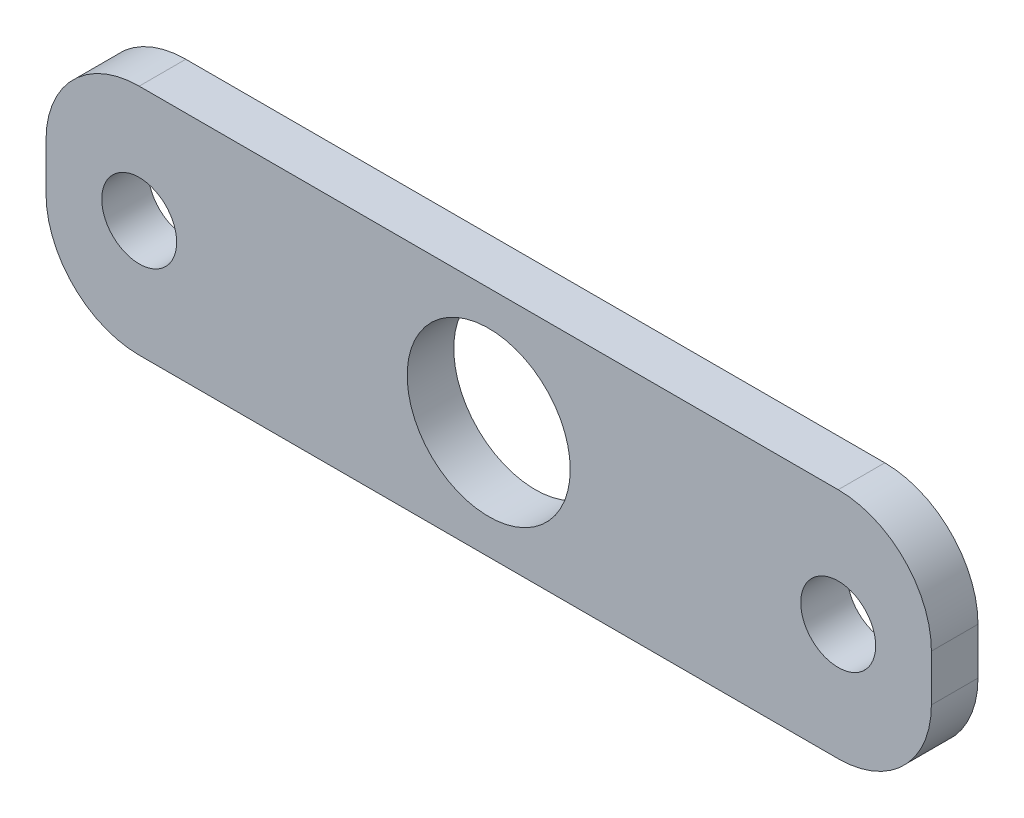
SolidWorks part; units mm, degrees
ref_plane "Front Plane" through (0, 0, 0) normal (0, 0, 1) x (1, 0, 0)
ref_plane "Top Plane" through (0, 0, 0) normal (0, 1, 0) x (1, 0, 0)
ref_plane "Right Plane" through (0, 0, 0) normal (1, 0, 0) x (0, 0, -1)
sketch "Sketch1" plane through (0, 0, 0) normal (0, 0, 1) x (1, 0, 0)
  line L0 (-23.8125, 0) -> (23.8125, 0) construction
  line L2 (-30.1625, 7.9375) -> (30.1625, 7.9375)
  line L3 (-30.1625, 7.9375) -> (-30.1625, -7.9375)
  line L4 (-30.1625, -7.9375) -> (30.1625, -7.9375)
  line L5 (30.1625, 7.9375) -> (30.1625, -7.9375)
  line L6 (-30.1625, 7.9375) -> (30.1625, -7.9375) construction
  line L7 (-30.1625, -7.9375) -> (30.1625, 7.9375) construction
  line L8 (-30.1625, 12.7) -> (30.1625, 12.7) construction
  line L9 (-30.1625, 12.7) -> (-30.1625, -12.7) construction
  line L10 (-30.1625, -12.7) -> (30.1625, -12.7) construction
  line L11 (30.1625, 12.7) -> (30.1625, -12.7) construction
  line L12 (-30.1625, 12.7) -> (30.1625, -12.7) construction
  line L13 (-30.1625, -12.7) -> (30.1625, 12.7) construction
  circle A0 centre (0, 0) radius 5.5562
  circle A1 centre (23.8125, 0) radius 2.5527
  circle A2 centre (-23.8125, 0) radius 2.5527
  circle A3 centre (0, 0) radius 6.3489 construction
  circle A4 centre (0, 0) radius 7.9364 construction
  circle A5 centre (-23.8125, 0) radius 4.1402
  circle A6 centre (23.8125, 0) radius 4.1402
  arc A8 (-1.2652, -7.8349) -> (1.2652, -7.8349) centre (0, 0) ccw
  point P0 (0, 0)
  dimension "D3" = 47.625
  dimension "D4" = 5.1054
  dimension "D5" = 11.1125
  dimension "D1" = 60.325
  dimension "D2" = 25.4
  dimension "D6" = 1.5875
  dimension "D7" = 15.875
  dimension "D9" = 1.5875
extrude "Boss-Extrude1" add sketch "Sketch1" along normal mid plane 3.175
fillet "Fillet3" radius 6.35 4 edges at (30.1625, -7.9375, 0) (-30.1625, -7.9375, 0) (30.1625, 7.9375, 0) (-30.1625, 7.9375, 0)
